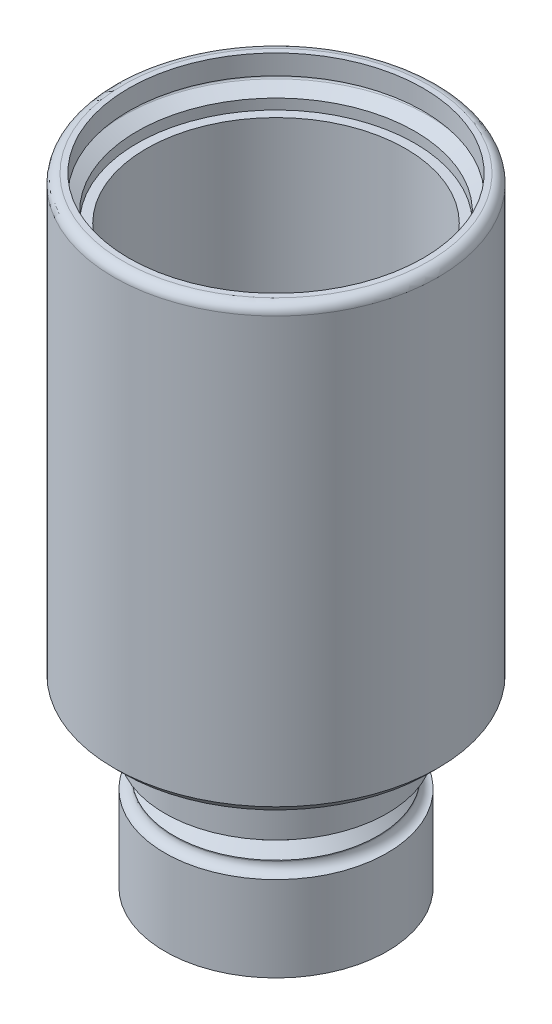
SolidWorks part; units mm, degrees
ref_plane "Спереди" through (0, 0, 0) normal (0, 0, 1) x (1, 0, 0)
ref_plane "Сверху" through (0, 0, 0) normal (0, 1, 0) x (1, 0, 0)
ref_plane "Справа" through (0, 0, 0) normal (1, 0, 0) x (0, 0, -1)
sketch "Эскиз1" plane through (0, 0, 0) normal (0, 0, 1) x (1, 0, 0)
  line L0 (0, 0) -> (0, 66.8) construction
  line L1 (-15.9, 66.8) -> (-17.5, 66.8)
  line L2 (-17.5, 66.8) -> (-17.5, 18.9)
  line L3 (-17.5, 18.9) -> (-13.0009, 18.9)
  line L7 (-12, 0) -> (-7.5, 0)
  line L8 (-7.5, 0) -> (-7.5, 1.8)
  line L9 (-7.5, 1.8) -> (-9.75, 1.8)
  line L10 (-9.75, 1.8) -> (-9.75, 4.8)
  line L11 (-9.75, 4.8) -> (-7.5, 4.8)
  line L12 (-7.5, 4.8) -> (-7.5, 6.3)
  line L13 (-7.5, 6.3) -> (-9.75, 6.3)
  line L14 (-9.75, 6.3) -> (-9.75, 9.3)
  line L15 (-9.75, 9.3) -> (-7.5, 9.3)
  line L16 (-7.5, 9.3) -> (-7.5, 10.4)
  line L17 (-7.5, 10.4) -> (-7, 10.4)
  line L18 (-7, 10.4) -> (-7, 11.1)
  line L19 (-7, 15.4) -> (-6, 15.4)
  line L20 (-6, 15.4) -> (-6, 17.4622)
  line L21 (-6, 17.4622) -> (-9.5, 18.4)
  line L22 (-9.5, 18.4) -> (-9.5, 32.0536)
  line L23 (-9.5, 32.0536) -> (-10.1, 32.4)
  line L24 (-10.1, 32.4) -> (-10.1, 33.6)
  line L25 (-10.1, 33.6) -> (-9.5, 33.6)
  line L26 (-9.5, 33.6) -> (-9.5, 35.2999)
  line L28 (-14, 41.1) -> (-14, 62.1)
  line L29 (-14, 62.1) -> (-15, 62.1)
  line L30 (-15, 62.1) -> (-15, 63.2185)
  line L31 (-15, 63.2185) -> (-16.4, 64.0268)
  line L32 (-16.4, 64.3732) -> (-15.9, 64.6619)
  line L33 (-15.9, 64.6619) -> (-15.9, 66.8)
  line L34 (-16.3, 64.2) -> (-16.5, 64.2) construction
  line L35 (-14, 41.1) -> (-11, 41.1)
  line L36 (-11, 41.1) -> (-9.5, 35.2999)
  line L37 (-13.0009, 18.9) -> (-12, 16.15)
  line L38 (-12, 16.15) -> (-12, 12.9)
  line L39 (-12, 12.9) -> (-9.9, 12.9)
  line L40 (-9.9, 12.9) -> (-9.9, 11.4)
  line L41 (-9.9, 11.4) -> (-11, 10.3)
  line L42 (-12, 9.2) -> (-12, 0)
  line L43 (-7, 12.3) -> (-7, 15.4)
  line L45 (-11, 10.2) -> (-11, 10.3)
  arc A0 (-16.4, 64.0268) -> (-16.4, 64.3732) centre (-16.3, 64.2) cw
  arc A1 (-7, 12.3) -> (-7, 11.1) centre (-7, 11.7) ccw
  arc A2 (-12, 9.2) -> (-11, 10.2) centre (-12, 10.2) ccw
  point P40 (-16.7, 64.2)
  point P41 (-16.5, 64.2)
  point P46 (-6.5, 15.4)
  dimension "D9" = 0.2
  dimension "D39" = 1.2
  dimension "D41" = 2
  dimension "D1" = 66.8
  dimension "D2" = 35
  dimension "D3" = 24
  dimension "D4" = 31.8
  dimension "D5" = 30
  dimension "D6" = 4.7
  dimension "D7" = 2.6
  dimension "D8" = 60
  dimension "D10" = 33
  dimension "D11" = 28
  dimension "D12" = 25.7
  dimension "D13" = 22
  dimension "D14" = 14.5
  dimension "D15" = 19
  dimension "D16" = 20
  dimension "D17" = 18.9
  dimension "D18" = 2.75
  dimension "D19" = 19.8
  dimension "D20" = 45
  dimension "D21" = 12.9
  dimension "D22" = 2.7
  dimension "D23" = 15
  dimension "D24" = 20.2
  dimension "D25" = 1.2
  dimension "D26" = 33.2
  dimension "D27" = 60
  dimension "D28" = 48.4
  dimension "D29" = 75
  dimension "D30" = 12
  dimension "D31" = 19.5
  dimension "D32" = 1.8
  dimension "D33" = 3
  dimension "D34" = 1.5
  dimension "D35" = 3
  dimension "D36" = 14
  dimension "D37" = 15.4
  dimension "D38" = 10.4
  dimension "D40" = 11.7
  dimension "D42" = 1.5
revolve "Повернуть1" add sketch "Эскиз1" angle 360 about L0
chamfer "Фаска1" distance 1 angle 45 1 edges at (0, 18.9, -17.5)
fillet "Скругление1" radius 0.5 1 edges at (0, 0, -7.5)
fillet "Скругление2" radius 0.2 4 edges at (0, 9.3, -7.5) (0, 6.3, -7.5) (0, 4.8, -7.5) (0, 1.8, -7.5)
fillet "Скругление3" radius 0.4 4 edges at (0, 4.8, -9.75) (0, 1.8, -9.75) (0, 6.3, -9.75) (0, 9.3, -9.75)
fillet "Скругление4" radius 0.2 6 edges at (0, 41.1, -11) (0, 35.2999, -9.5) (0, 33.6, -9.5) (0, 33.6, -10.1) (0, 32.4, -10.1) (0, 32.0536, -9.5)
fillet "Скругление5" radius 1 1 edges at (0, 66.8, -17.5)
